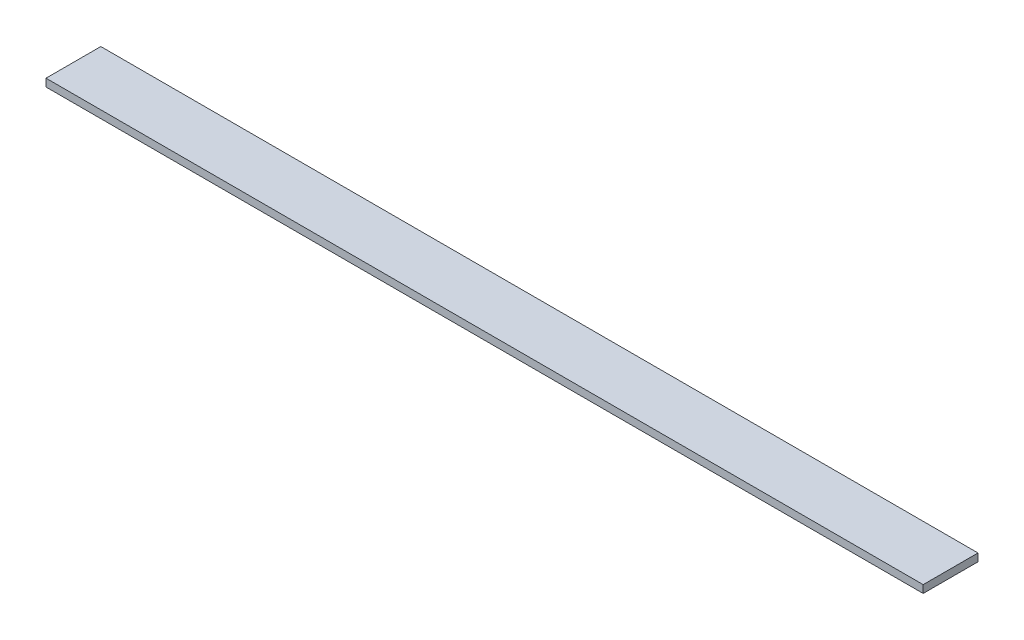
SolidWorks part; units mm, degrees
ref_plane "Front Plane" through (0, 0, 0) normal (0, 0, 1) x (1, 0, 0)
ref_plane "Top Plane" through (0, 0, 0) normal (0, 1, 0) x (1, 0, 0)
ref_plane "Right Plane" through (0, 0, 0) normal (1, 0, 0) x (0, 0, -1)
sketch "Sketch1" plane through (0, 0, 0) normal (0, 1, 0) x (1, 0, 0)
  line L1 (-40, -2.5) -> (40, -2.5)
  line L2 (-40, -2.5) -> (-40, 2.5)
  line L3 (-40, 2.5) -> (40, 2.5)
  line L4 (40, -2.5) -> (40, 2.5)
  line L5 (-40, -2.5) -> (40, 2.5) construction
  line L6 (-40, 2.5) -> (40, -2.5) construction
  point P0 (0, 0)
  dimension "D1" = 5
  dimension "D2" = 80
extrude "Boss-Extrude1" add sketch "Sketch1" along normal blind 0.7
